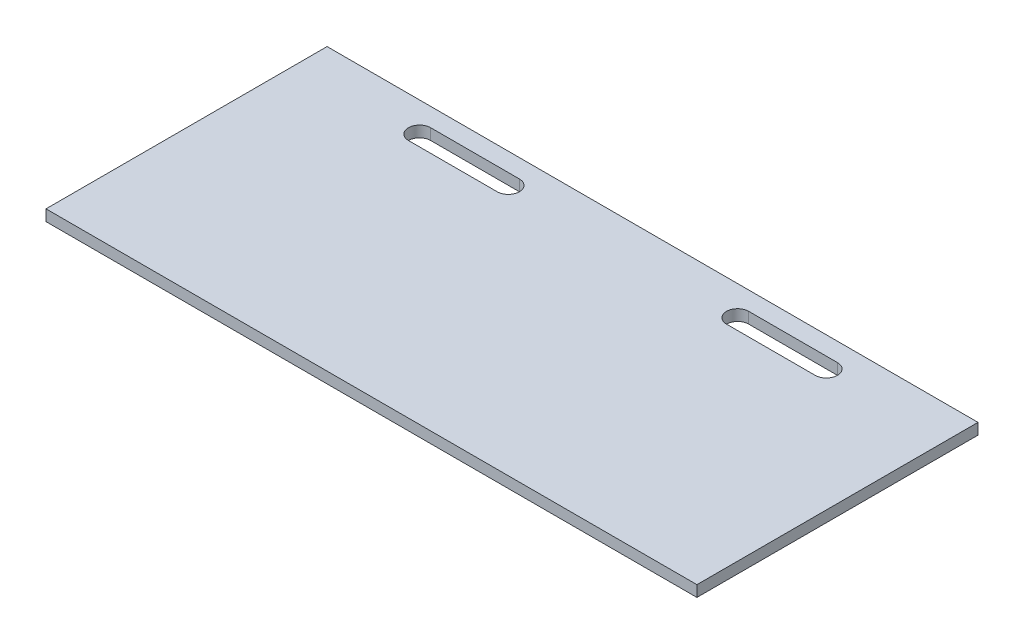
SolidWorks part; units mm, degrees
material "Pine"
ref_plane "Front Plane" through (0, 0, 0) normal (0, 0, 1) x (1, 0, 0)
ref_plane "Top Plane" through (0, 0, 0) normal (0, 1, 0) x (1, 0, 0)
ref_plane "Right Plane" through (0, 0, 0) normal (1, 0, 0) x (0, 0, -1)
sketch "Sketch1" plane through (0, 0, 0) normal (0, 1, 0) x (1, 0, 0)
  line L1 (-558.8, -241.3) -> (558.8, -241.3)
  line L2 (-558.8, -241.3) -> (-558.8, 241.3)
  line L3 (-558.8, 241.3) -> (558.8, 241.3)
  line L4 (558.8, -241.3) -> (558.8, 241.3)
  line L5 (-558.8, -241.3) -> (558.8, 241.3) construction
  line L6 (-558.8, 241.3) -> (558.8, -241.3) construction
  point P0 (0, 0)
  dimension "D1" = 482.6
  dimension "D2" = 1117.6
extrude "Boss-Extrude1" add sketch "Sketch1" along normal mid plane 19.05 contours L3 L4 L1 L2
sketch "Sketch2" plane through (0, -9.525, 0) normal (0, -1, 0) x (1, 0, 0)
  line L0 (0, -241.3) -> (0, 241.3) construction
  line L1 (-349.25, -171.45) -> (-196.85, -171.45)
  line L2 (-349.25, -171.45) -> (-349.25, -209.55) construction
  line L3 (-349.25, -209.55) -> (-196.85, -209.55)
  line L4 (-196.85, -171.45) -> (-196.85, -209.55) construction
  line L5 (-349.25, -171.45) -> (-196.85, -209.55) construction
  line L6 (-349.25, -209.55) -> (-196.85, -171.45) construction
  line L7 (196.85, -171.45) -> (349.25, -171.45)
  line L8 (196.85, -171.45) -> (196.85, -209.55) construction
  line L9 (196.85, -209.55) -> (349.25, -209.55)
  line L10 (349.25, -171.45) -> (349.25, -209.55) construction
  line L11 (196.85, -171.45) -> (349.25, -209.55) construction
  line L12 (196.85, -209.55) -> (349.25, -171.45) construction
  line L13 (-558.8, -241.3) -> (558.8, -241.3) construction
  line L14 (-558.8, 241.3) -> (558.8, 241.3) construction
  arc A0 (349.25, -171.45) -> (349.25, -209.55) centre (349.25, -190.5) cw
  arc A1 (196.85, -171.45) -> (196.85, -209.55) centre (196.85, -190.5) ccw
  arc A2 (-196.85, -171.45) -> (-196.85, -209.55) centre (-196.85, -190.5) cw
  arc A3 (-349.25, -209.55) -> (-349.25, -171.45) centre (-349.25, -190.5) cw
  point P0 (-273.05, -190.5)
  point P5 (273.05, -190.5)
  dimension "D1" = 38.1
  dimension "D2" = 152.4
  dimension "D3" = 50.8
  dimension "D4" = 546.1
extrude "Cut-Extrude1" cut sketch "Sketch2" against normal through all both
